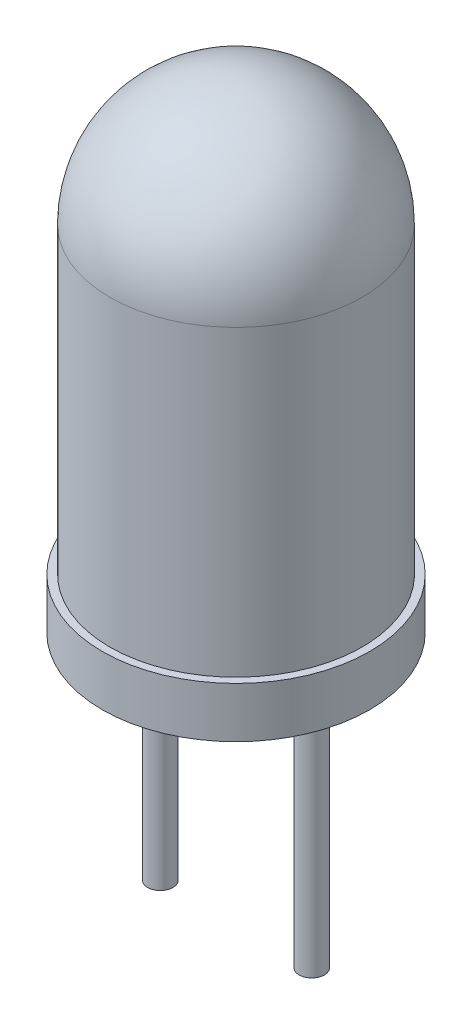
SolidWorks part; units mm, degrees
material "Acrylic (Medium-high impact)"
ref_plane "Front Plane" through (0, 0, 0) normal (0, 0, 1) x (1, 0, 0)
ref_plane "Top Plane" through (0, 0, 0) normal (0, 1, 0) x (1, 0, 0)
ref_plane "Right Plane" through (0, 0, 0) normal (1, 0, 0) x (0, 0, -1)
sketch "Sketch1" plane through (0, 0, 0) normal (1, 0, 0) x (0, 0, -1)
  line L0 (0, 5.1503) -> (0, -4.6232) construction
  line L1 (-2.5, -0.4318) -> (-2.5, 5.5682)
  line L2 (-2.5, -0.4318) -> (-2.65, -0.4318)
  line L3 (-2.65, -0.4318) -> (-2.65, -1.4318)
  line L4 (-2.65, -1.4318) -> (0, -1.4318)
  line L5 (0, -1.4318) -> (0, 1.6313)
  line L6 (0, 8.0682) -> (0, 1.6313)
  arc A0 (-2.5, 5.5682) -> (0, 8.0682) centre (0, 5.5682) cw
  dimension "D1" = 5.3
  dimension "D2" = 1
  dimension "D3" = 2.5
  dimension "D4" = 6
revolve "Revolve1" add sketch "Sketch1" angle 360 about L6
sketch "Sketch2" plane through (0, -1.4318, 0) normal (0, -1, 0) x (1, 0, 0)
  line L0 (0, 2.65) -> (0, -2.65) construction
  line L1 (-2.65, 0) -> (2.65, 0) construction
  circle A0 centre (0, 0) radius 2.65 construction
  circle A1 centre (-1.5, 0) radius 0.25
  circle A2 centre (1.5, 0) radius 0.25
  dimension "D1" = 0.5
  dimension "D2" = 3
extrude "Boss-Extrude1" add sketch "Sketch2" along normal blind 5
